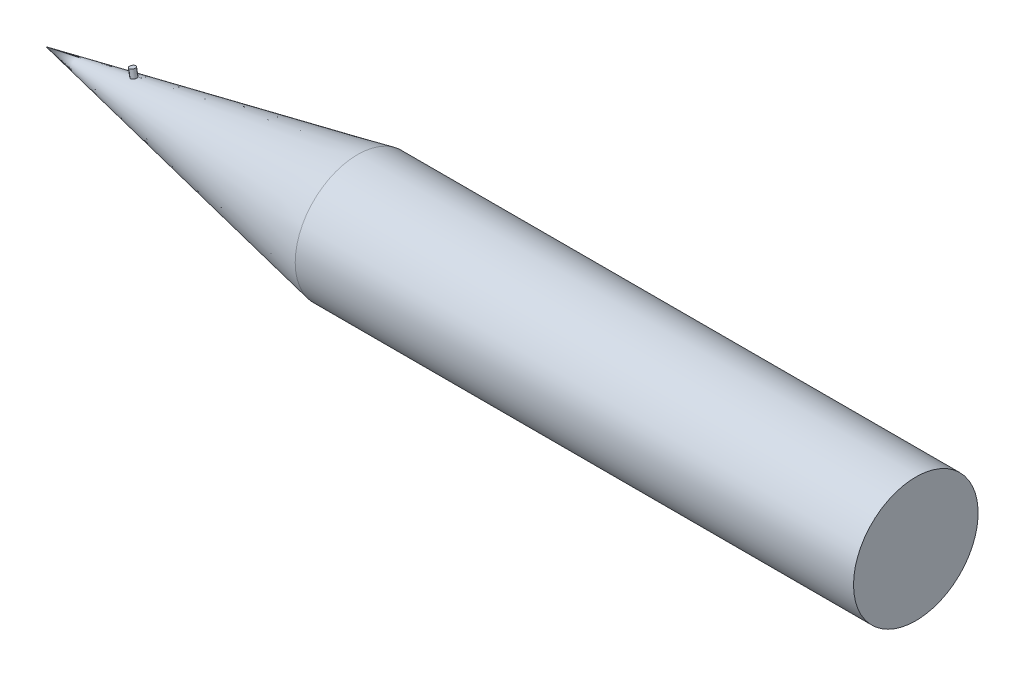
SolidWorks part; units mm, degrees
ref_plane "前基準面" through (0, 0, 0) normal (0, 0, 1) x (1, 0, 0)
ref_plane "上基準面" through (0, 0, 0) normal (0, 1, 0) x (1, 0, 0)
ref_plane "右基準面" through (0, 0, 0) normal (1, 0, 0) x (0, 0, -1)
sketch "草圖1" plane through (0, 0, 0) normal (0, 0, 1) x (1, 0, 0)
  line L1 (0, 0) -> (15.8756, 3.1751)
  line L4 (15.8756, 3.1751) -> (15.8756, 0)
  line L5 (0, 0) -> (44.33, 0) construction
  line L6 (15.8756, 3.1751) -> (44.33, 3.1751)
  line L7 (44.33, 3.1751) -> (44.33, -3.1751)
  line L8 (15.8756, -3.1751) -> (44.33, -3.1751)
  line L9 (0, 0) -> (15.8756, -3.1751)
  point P3 (4.4832, 0.8966)
  dimension "D1" = 44.33
  dimension "D2" = 16.19
  dimension "D4" = 4.572
ref_plane "平面1" through (0, 0, 0) normal (-0.1961, 0.9806, 0) x (0.9806, 0.1961, 0)
sketch "草圖2" plane through (0, 0, 0) normal (-0.1961, 0.9806, 0) x (0.9806, 0.1961, 0)
  circle A0 centre (4.572, 0) radius 0.15
extrude "填料-伸長1" add sketch "草圖2" along normal blind 0.41 separate body
revolve "旋轉1" add sketch "草圖1" angle 360 about L5
